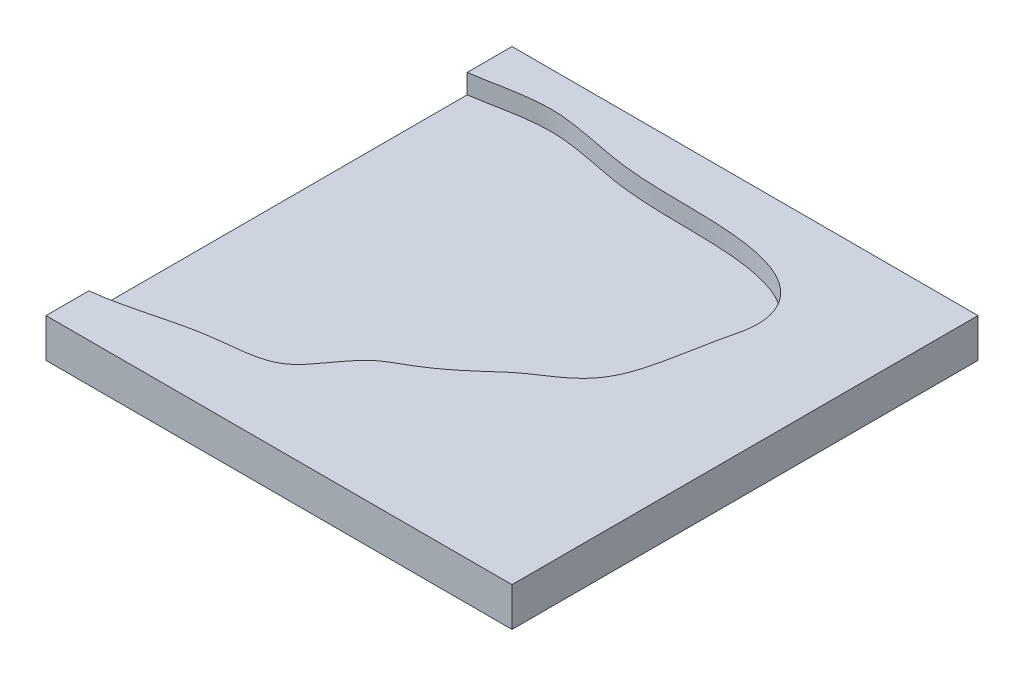
SolidWorks part; units mm, degrees
ref_plane "Piano frontale" through (0, 0, 0) normal (0, 0, 1) x (1, 0, 0)
ref_plane "Piano superiore" through (0, 0, 0) normal (0, 1, 0) x (1, 0, 0)
ref_plane "Piano destro" through (0, 0, 0) normal (1, 0, 0) x (0, 0, -1)
sketch "Schizzo2" plane through (0, 0, 0) normal (0, 1, 0) x (1, 0, 0)
  line L0 (-2.6639, -29.6899) -> (117.3361, -29.6899)
  line L1 (117.3361, -29.6899) -> (117.3361, -149.6899)
  line L2 (117.3361, -149.6899) -> (-2.6639, -149.6899)
  line L3 (-2.6639, -149.6899) -> (-2.6639, -29.6899)
  dimension "D1" = 120
  dimension "D2" = 120
extrude "Estrusione-Estrusione2" add sketch "Schizzo2" along normal blind 10
sketch "Schizzo3" plane through (0, 10, 0) normal (0, 1, 0) x (1, 0, 0)
  line L0 (117.3361, -38.6439) -> (-2.6639, -38.6439) construction
  line L1 (117.3361, -149.6899) -> (117.3361, -29.6899) construction
  line L2 (-2.6639, -29.6899) -> (-2.6639, -149.6899) construction
  line L3 (-2.6639, -38.6439) -> (-2.6639, -138.6439) construction
  line L4 (-2.6639, -138.6439) -> (117.3361, -138.6439) construction
  line L5 (87.2887, -249.679) -> (983.2887, -249.679) construction
  line L6 (-172.811, -0.173) -> (723.189, -0.173) construction
  line L7 (-165.1322, 59.6149) -> (730.8678, 59.6149) construction
  line L8 (224, 365.5) -> (1120, 365.5) construction
  line L9 (224, 365.5) -> (1120, 365.5) construction
  line L10 (-325.0687, -28.1877) -> (570.9313, -28.1877) construction
  line L11 (12.2651, 134.494) -> (906.0825, 196.9958) construction
  line L12 (-2.6639, -41.221) -> (-2.6639, -138.6439)
  line L13 (90.8706, -29.6899) -> (90.8706, -138.6439) construction
  line L14 (117.3361, -29.6899) -> (-2.6639, -29.6899) construction
  line L15 (117.3361, -89.6899) -> (-176.1198, -89.6899) construction
  spline S0 degree 3 poles (-2.6639, -41.221) (3.3535, -40.4166) (16.3405, -36.6755) (38.9105, -43.2358) (63.3358, -41.9486) (86.6024, -45.3776) (92.0619, -58.1756) (88.2777, -72.1562) (85.6431, -94.5903) (74.3391, -98.3953) (64.9766, -106.818) (59.2575, -111.939) (46.9509, -118.4293) (41.016, -130.6524) (33.0341, -132.1478) (16.0098, -133.8686) (5.7569, -137.7478) (-2.6639, -138.6439) knots 0 0 0 0 0.094416 0.184088 0.301356 0.42662 0.503603 0.520544 0.596031 0.700435 0.720928 0.792072 0.806902 0.860339 0.916687 0.930653 1 1 1 1
  dimension "D1" = 100
  dimension "D2" = 93.5345
extrude "Taglio-Estrusione1" cut sketch "Schizzo3" against normal blind 5
sketch "Schizzo4" plane through (0, 0, 0) normal (0, -1, 0) x (1, 0, 0)
  line L0 (57.3361, 149.6899) -> (57.3361, 29.6899) construction
  line L1 (-2.6639, 149.6899) -> (117.3361, 149.6899) construction
  line L2 (117.3361, 29.6899) -> (-2.6639, 29.6899) construction
  line L4 (117.3361, 149.6899) -> (117.3361, 29.6899) construction
  line L5 (117.3361, 89.6899) -> (-2.6639, 89.6899) construction
  line L6 (-2.6639, 29.6899) -> (-2.6639, 149.6899) construction
  point P6 (57.3361, 109.6899)
  point P13 (57.3361, 69.6899)
  dimension "D1" = 20
  dimension "D2" = 20
hole_wizard "Foro per Vite M2.5-2" positions "Schizzo3D5" profile "Schizzo9" hole size "M2.5" standard "IS"
sketch3d "Schizzo3D5"
  point P0 (57.3361, 0, 69.6899)
  point P3 (57.3361, 0, 109.6899)
sketch "Schizzo9" plane through (57.3361, 0, 69.6899) normal (1, 0, 0) x (0, 0, -1)
  line L0 (0, 0) -> (0, 4.9313)
  line L1 (0, 4.9313) -> (1.55, 4)
  line L2 (1.55, 4) -> (1.55, 0)
  line L5 (1.55, 0) -> (0, 0)
  line L10 (0, 4.9313) -> (-1.55, 4) construction
  line L11 (0, -6.35) -> (0, 107.95) construction
  dimension "Hole Dia." = 3.1
  dimension "Hole Depth" = 4
  dimension "Drill Angle" = 118
